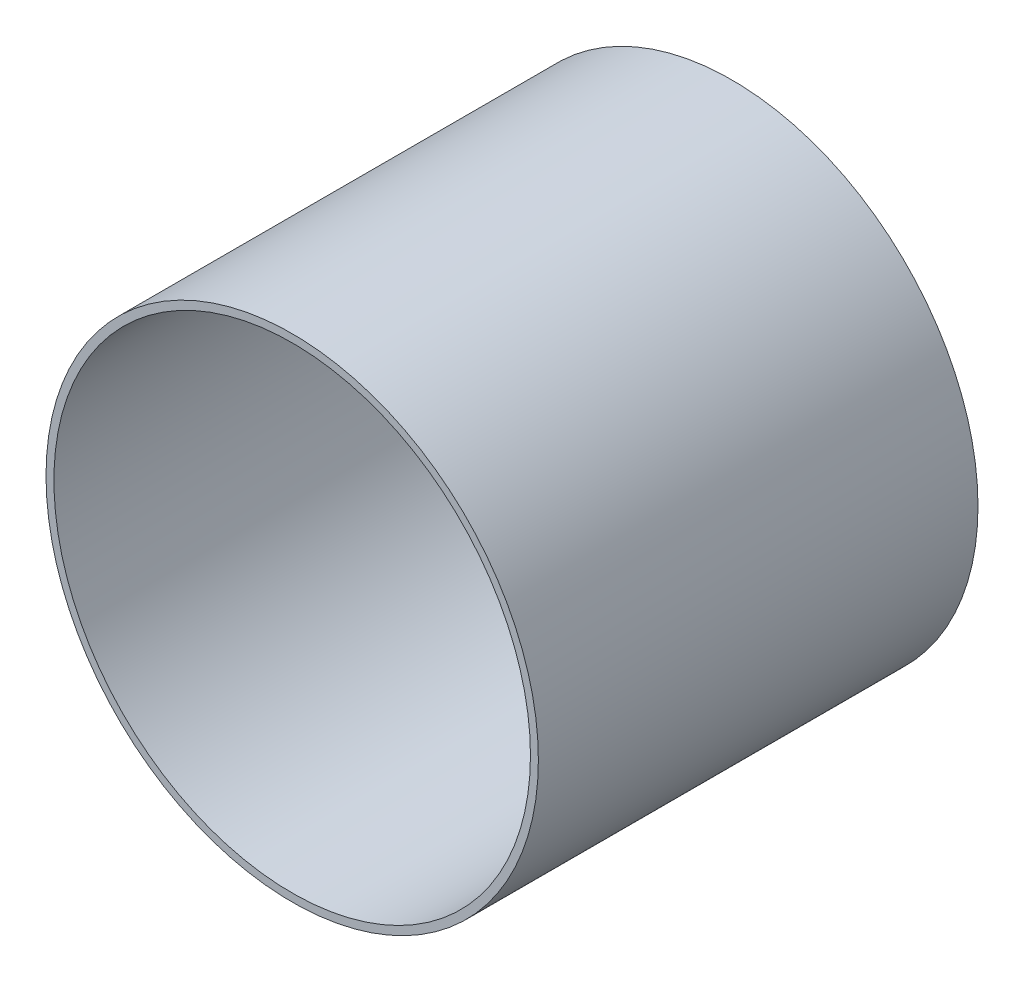
SolidWorks part; units mm, degrees
ref_plane "Front Plane" through (0, 0, 0) normal (0, 0, 1) x (1, 0, 0)
ref_plane "Top Plane" through (0, 0, 0) normal (0, 1, 0) x (1, 0, 0)
ref_plane "Right Plane" through (0, 0, 0) normal (1, 0, 0) x (0, 0, -1)
sketch "Sketch1" plane through (0, 0, 0) normal (0, 0, 1) x (1, 0, 0)
  circle A0 centre (0, 0) radius 13.55
  circle A1 centre (0, 0) radius 14
  dimension "D1" = 28
  dimension "D2" = 27.1
extrude "Boss-Extrude1" add sketch "Sketch1" along normal blind 25
